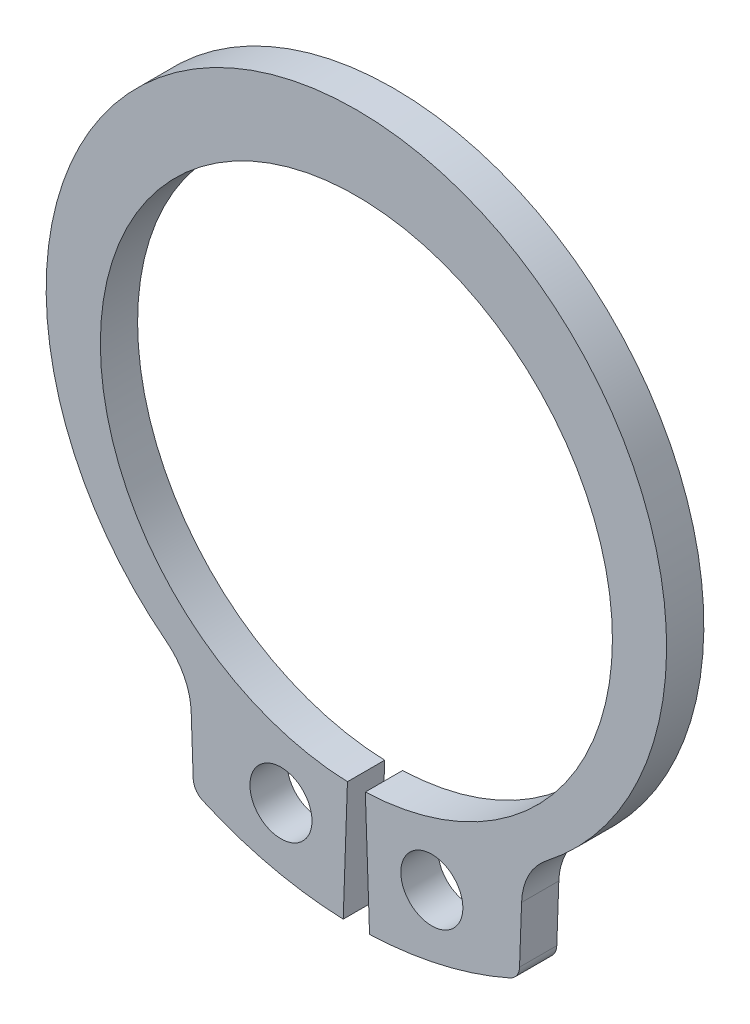
SolidWorks part; units mm, degrees
ref_plane "Front Plane" through (0, 0, 0) normal (0, 0, 1) x (1, 0, 0)
ref_plane "Top Plane" through (0, 0, 0) normal (0, 1, 0) x (1, 0, 0)
ref_plane "Right Plane" through (0, 0, 0) normal (1, 0, 0) x (0, 0, -1)
sketch "Sketch1" plane through (0, 0, 0) normal (0, 0, 1) x (1, 0, 0)
  line L0 (0, 0.0662) -> (-7.1447, -4.0588) construction
  line L1 (0, 12.15) -> (0, -12.0838) construction
  line L2 (-5.2462, -10.9011) -> (-5.3591, -7.7173) construction
  line L3 (0, 10.7162) -> (0, 8.3162)
  line L4 (-5.3591, -7.7173) -> (-6.0397, -8.7057) construction
  line L5 (-5.3591, -7.7173) -> (0, 0.0662) construction
  line L6 (0, 8.3162) -> (0, 10.7162) construction
  line L7 (0, 10.7162) -> (0, 9.5162) construction
  line L8 (0, -8.1838) -> (0, -12.0838) construction
  line L9 (-2.8963, -11.7412) -> (0, 0.0662) construction
  line L10 (0, 0.0662) -> (-0.4243, -12.0838) construction
  line L11 (-5.2462, -10.9011) -> (0, 0.0662) construction
  line L12 (-5.3261, -8.6492) -> (-6.1221, -7.1812) construction
  line L13 (-5.7241, -7.9152) -> (-5.3591, -7.7173) construction
  line L14 (-1.9654, -7.9463) -> (-2.8963, -11.7412) construction
  line L15 (-2.4308, -9.8438) -> (-1.4596, -10.082) construction
  line L16 (-0.4243, -12.0838) -> (-0.2879, -8.1788)
  line L17 (-5.2462, -10.9011) -> (-5.3591, -7.7173)
  arc A0 (0, 10.7162) -> (-5.3591, -7.7173) centre (0, 0.7204) ccw construction
  circle A2 centre (0, 0.0662) radius 10.65 construction
  arc A3 (-5.2462, -10.9011) -> (-0.4243, -12.0838) centre (0, 0.0662) ccw construction
  circle A4 centre (0, 0.0662) radius 8.25 construction
  circle A6 centre (-2.4308, -9.8438) radius 1 construction
  arc A7 (-6.1221, -7.1812) -> (-5.3261, -8.6492) centre (-7.3913, -8.8192) cw construction
  circle A9 centre (0, 0.0662) radius 9 construction
  circle A10 centre (0, 0.0662) radius 8.5 construction
  circle A11 centre (-2.4308, -9.8438) radius 1
  arc A12 (-0.4243, -12.0838) -> (-5.2462, -10.9011) centre (0, 0.0662) cw
  arc A13 (0, 8.3162) -> (-0.2879, -8.1788) centre (0, 0.0662) ccw
  arc A14 (-5.3591, -7.7173) -> (0, 10.7162) centre (0, 0.7204) cw
  point P5 (-7.1447, -4.0588)
  point P24 (-4.5957, -9.5412)
  point P35 (0, 10.7162)
  point P36 (0, 8.3162)
  point P37 (0, -8.1838)
  point P38 (0, -12.0838)
  dimension "Hole Diameter" = 2
  dimension "D10" = 2.0722
  dimension "For OD" = 18
  dimension "ID" = 16.5
  dimension "Max Sec." = 2.4
  dimension "Lug Height" = 3.9
  dimension "D6" = 2
  dimension "D5" = 3.1858
  dimension "D8" = 1.67
  dimension "D3" = 120
  dimension "D2" = 5
  dimension "D4" = 1.67
extrude "Boss-Extrude1" add sketch "Sketch1" along normal blind 1.2
fillet "Fillet1" radius 2.07 1 edges at (-5.3591, -7.7173, 0.6)
fillet "Fillet4" radius 0.52 1 edges at (-5.2462, -10.9011, 0.6)
mirror "Mirror1" about plane through (0, 10.7162, 1.2) normal (-1, 0, 0) of "Fillet1", "Fillet4", "Boss-Extrude1"
equation "\"For Groove Diameter@Sketch1\"=\"groove_d\""
equation "\"For OD@Sketch1\"=\"shaft_od\""
equation "\"Max Sec.@Sketch1\"=\"top_width\""
equation "\"ID@Sketch1\"=\"inner_d\""
equation "\"Lug Height@Sketch1\"=\"lug_height\""
equation "\"Hole Diameter@Sketch1\"=\"hole_d\""
equation "\"D3@Sketch1\"=\"angle\""
equation "\"D6@Sketch1\"=\"lug_inner_angle\""
equation "\"D2@Sketch1\"=\"lug_width\""
equation "\"D4@Sketch1\"=\"edge_width2\""
equation "\"D8@Sketch1\"=\"edge_width\""
equation "\"groove_d\"=17.00"
equation "\"shaft_od\"=18.00"
equation "\"inner_d\"=16.50"
equation "\"top_width\"=2.40"
equation "\"lug_height\"=3.90"
equation "\"hole_d\"=2.00"
equation "\"lug_inner_angle\"=2.00"
equation "\"lug_width\"=5.00"
equation "\"lug_height2\"=3.18"
equation "\"lug_radius\"=0.52"
equation "\"edge_width\"=1.67"
equation "\"edge_width2\"=1.67"
equation "\"edge_radius\"=2.07"
equation "\"angle\"=120.00"
equation "\"groove_t\"=1.30"
equation "\"ring_thickness\"=1.20"
equation "\"D1@Boss-Extrude1\"=\"ring_thickness\""
equation "\"D1@Fillet1\"=\"edge_radius\""
equation "\"D1@Fillet4\"=\"lug_radius\""
